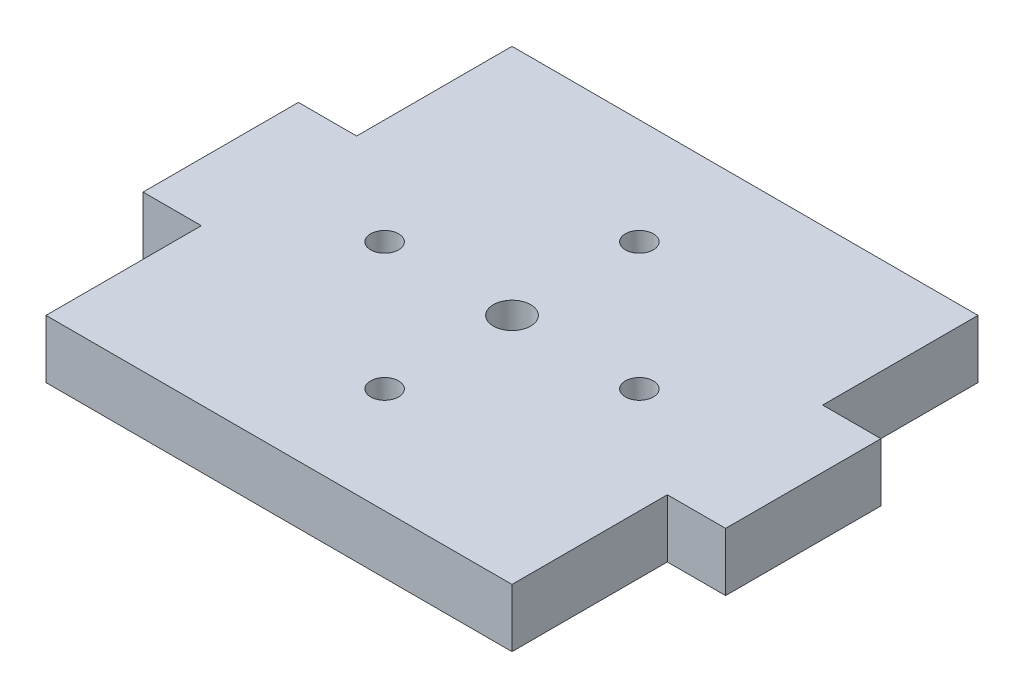
SolidWorks part; units mm, degrees
ref_plane "Front Plane" through (0, 0, 0) normal (0, 0, 1) x (1, 0, 0)
ref_plane "Top Plane" through (0, 0, 0) normal (0, 1, 0) x (1, 0, 0)
ref_plane "Right Plane" through (0, 0, 0) normal (1, 0, 0) x (0, 0, -1)
sketch "Sketch1" plane through (0, 0, 0) normal (0, 1, 0) x (1, 0, 0)
  line L0 (0, 0) -> (0, 12.7)
  line L1 (0, 12.7) -> (-4.7625, 12.7)
  line L2 (-4.7625, 12.7) -> (-4.7625, 25.4)
  line L3 (-4.7625, 25.4) -> (0, 25.4)
  line L4 (0, 25.4) -> (0, 38.1)
  line L5 (0, 38.1) -> (38.1, 38.1)
  line L6 (38.1, 38.1) -> (38.1, 25.4)
  line L7 (38.1, 25.4) -> (42.8625, 25.4)
  line L8 (42.8625, 25.4) -> (42.8625, 12.7)
  line L9 (42.8625, 12.7) -> (38.1, 12.7)
  line L10 (38.1, 12.7) -> (38.1, 0)
  line L11 (38.1, 0) -> (0, 0)
  line L12 (-4.7625, 19.05) -> (19.05, 19.05) construction
  line L13 (19.05, 19.05) -> (19.05, 0) construction
  line L14 (19.05, 19.05) -> (29.464, 19.05) construction
  line L15 (19.05, 19.05) -> (19.05, 29.464) construction
  line L16 (8.636, 19.05) -> (19.05, 19.05) construction
  line L17 (19.05, 8.636) -> (19.05, 19.05) construction
  circle A0 centre (19.05, 19.05) radius 1.524
  circle A1 centre (29.464, 19.05) radius 1.143
  circle A6 centre (19.05, 8.636) radius 1.143
  circle A7 centre (8.636, 19.05) radius 1.143
  circle A8 centre (19.05, 29.464) radius 1.143
  point P28 (19.05, 19.05)
  dimension "D1" = 2.286
  dimension "D2" = 3.048
  dimension "D5" = 38.1
  dimension "D3" = 20.828
  dimension "D6" = 38.1
  dimension "D7" = 4
  dimension "D4" = 4.7625
  dimension "D8" = 12.7
extrude "Boss-Extrude1" add sketch "Sketch1" along normal blind 4.7625
